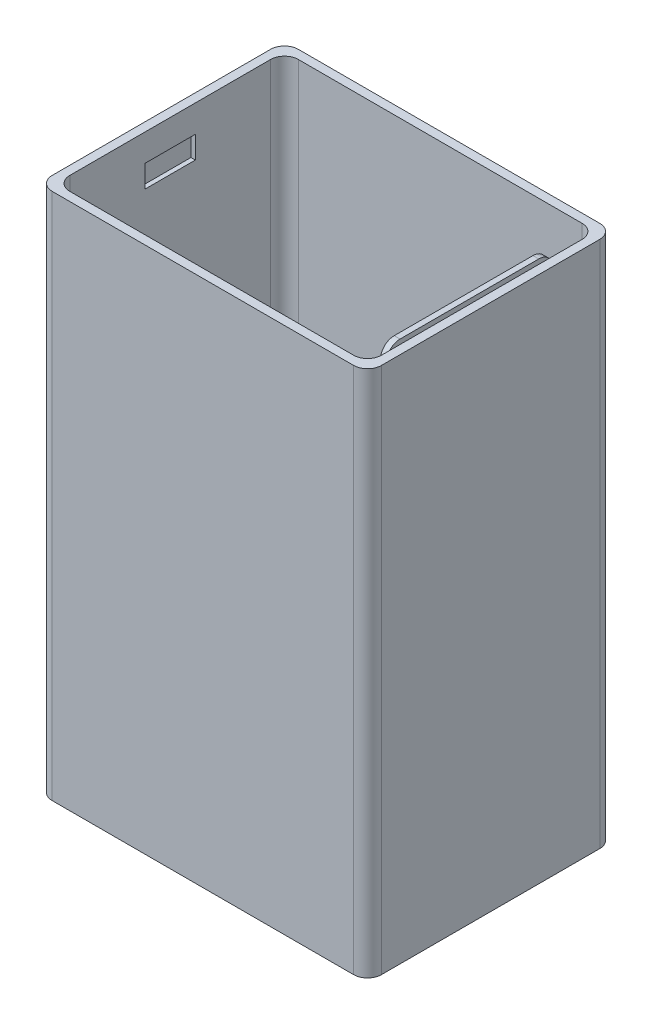
SolidWorks part; units mm, degrees
ref_plane "Front Plane" through (0, 0, 0) normal (0, 0, 1) x (1, 0, 0)
ref_plane "Top Plane" through (0, 0, 0) normal (0, 1, 0) x (1, 0, 0)
ref_plane "Right Plane" through (0, 0, 0) normal (1, 0, 0) x (0, 0, -1)
sketch "Sketch1" plane through (0, 0, 0) normal (0, 1, 0) x (1, 0, 0)
  line L0 (-6.35, 6.35) -> (-6.35, -171.3484)
  line L1 (0, 0) -> (224.9932, 0)
  line L2 (0, 0) -> (0, -164.9984)
  line L3 (0, -164.9984) -> (224.9932, -164.9984)
  line L4 (224.9932, 0) -> (224.9932, -164.9984)
  line L5 (-6.35, -171.3484) -> (231.3432, -171.3484)
  line L6 (231.3432, 6.35) -> (231.3432, -171.3484)
  line L7 (-6.35, 6.35) -> (231.3432, 6.35)
  dimension "D1" = 224.9932
  dimension "D2" = 164.9984
  dimension "D3" = 6.35
extrude "Boss-Extrude1" add sketch "Sketch1" along normal blind 374.65
sketch "Sketch4" plane through (224.9932, 0, 0) normal (-1, 0, 0) x (0, 0, 1)
  line L0 (164.9984, 0) -> (0, 0) construction
  line L1 (28.7274, 0) -> (136.1694, 0)
  line L2 (28.7274, 0) -> (28.7274, 374.65)
  line L3 (28.7274, 374.65) -> (136.1694, 374.65)
  line L4 (136.1694, 0) -> (136.1694, 374.65)
  line L5 (164.9984, 374.65) -> (0, 374.65) construction
  line L8 (164.9984, 374.65) -> (164.9984, 0) construction
  dimension "D1" = 107.442
  dimension "D2" = 28.829
extrude "Boss-Extrude2" add sketch "Sketch4" along normal blind 9.017
sketch "Sketch5" plane through (215.9762, 0, 0) normal (-1, 0, 0) x (0, 0, 1)
  line L0 (136.1694, 374.65) -> (28.7274, 374.65) construction
  line L5 (142.5194, 0) -> (22.3774, 0)
  line L6 (142.5194, 0) -> (142.5194, 374.65)
  line L7 (142.5194, 374.65) -> (22.3774, 374.65)
  line L8 (22.3774, 0) -> (22.3774, 374.65)
  line L9 (28.7274, 0) -> (136.1694, 0) construction
  line L11 (164.9984, 374.65) -> (164.9984, 0) construction
  line L12 (136.1694, 0) -> (136.1694, 374.65) construction
  line L13 (28.7274, 374.65) -> (28.7274, 0) construction
  point P5 (0, 0)
  dimension "D1" = 6.35
  dimension "D2" = 6.35
extrude "Boss-Extrude3" add sketch "Sketch5" along normal blind 4.191
sketch "Sketch7" plane through (0, 374.65, 0) normal (0, 1, 0) x (1, 0, 0)
  line L1 (215.9762, -136.1694) -> (224.9932, -136.1694)
  line L2 (215.9762, -136.1694) -> (215.9762, -28.7274)
  line L3 (215.9762, -28.7274) -> (224.9932, -28.7274)
  line L4 (224.9932, -136.1694) -> (224.9932, -28.7274)
extrude "Cut-Extrude1" cut sketch "Sketch7" against normal blind 21.59
sketch "Sketch10" plane through (0, 374.65, 0) normal (0, 1, 0) x (1, 0, 0)
  line L1 (211.7852, -142.5194) -> (215.9762, -142.5194)
  line L2 (211.7852, -142.5194) -> (211.7852, -22.3774)
  line L3 (211.7852, -22.3774) -> (215.9762, -22.3774)
  line L4 (215.9762, -142.5194) -> (215.9762, -22.3774)
extrude "Cut-Extrude2" cut sketch "Sketch10" against normal blind 5.588
fillet "Fillet1" radius 10 1 edges at (231.3432, 187.325, 171.3484)
fillet "Fillet2" radius 10 1 edges at (224.9932, 187.325, 164.9984)
fillet "Fillet3" radius 10 2 edges at (231.3432, 187.325, -6.35) (224.9932, 187.325, 0)
fillet "Fillet4" radius 10 2 edges at (-6.35, 187.325, 171.3484) (0, 187.325, 164.9984)
fillet "Fillet5" radius 10 2 edges at (0, 187.325, 0) (-6.35, 187.325, -6.35)
fillet "Fillet6" radius 10 2 edges at (220.4847, 353.06, 136.1694) (220.4847, 353.06, 28.7274)
fillet "Fillet7" radius 10 2 edges at (213.8807, 369.062, 22.3774) (213.8807, 369.062, 142.5194)
sketch "Sketch11" plane through (211.7852, 0, 0) normal (-1, 0, 0) x (0, 0, 1)
  line L0 (22.3774, 0) -> (142.5194, 0) construction
  line L1 (57.0484, 0) -> (107.8484, 0)
  line L2 (57.0484, 0) -> (57.0484, 15.24)
  line L3 (57.0484, 15.24) -> (107.8484, 15.24)
  line L4 (107.8484, 0) -> (107.8484, 15.24)
  line L5 (142.5194, 0) -> (142.5194, 359.062) construction
  dimension "D1" = 15.24
  dimension "D2" = 50.8
  dimension "D3" = 34.671
extrude "Boss-Extrude4" add sketch "Sketch11" along normal blind 19.9898
fillet "Fillet10" radius 10 2 edges at (191.7954, 7.62, 107.8484) (191.7954, 7.62, 57.0484)
fillet "Fillet11" radius 10 5 edges at (206.7903, 15.24, 107.8484) (194.7243, 15.24, 104.9195) (206.7903, 15.24, 57.0484) (194.7243, 15.24, 59.9773) (191.7954, 15.24, 82.4484)
sketch "Sketch12" plane through (0, 0, 0) normal (0, -1, 0) x (1, 0, 0)
  line L0 (231.3432, 161.3484) -> (231.3432, 3.65) construction
  line L1 (221.3432, -6.35) -> (3.65, -6.35) construction
  line L2 (-6.35, 3.65) -> (-6.35, 161.3484) construction
  line L3 (3.65, 171.3484) -> (221.3432, 171.3484) construction
  line L4 (231.3432, 161.3484) -> (231.3432, 3.65)
  line L5 (221.3432, -6.35) -> (3.65, -6.35)
  line L6 (-6.35, 3.65) -> (-6.35, 161.3484)
  line L7 (3.65, 171.3484) -> (221.3432, 171.3484)
  arc A0 (231.3432, 161.3484) -> (221.3432, 171.3484) centre (221.3432, 161.3484) ccw construction
  arc A1 (221.3432, -6.35) -> (231.3432, 3.65) centre (221.3432, 3.65) ccw construction
  arc A2 (-6.35, 3.65) -> (3.65, -6.35) centre (3.65, 3.65) ccw construction
  arc A3 (3.65, 171.3484) -> (-6.35, 161.3484) centre (3.65, 161.3484) ccw construction
  arc A4 (231.3432, 161.3484) -> (221.3432, 171.3484) centre (221.3432, 161.3484) ccw
  arc A5 (221.3432, -6.35) -> (231.3432, 3.65) centre (221.3432, 3.65) ccw
  arc A6 (-6.35, 3.65) -> (3.65, -6.35) centre (3.65, 3.65) ccw
  arc A7 (3.65, 171.3484) -> (-6.35, 161.3484) centre (3.65, 161.3484) ccw
extrude "Boss-Extrude5" add sketch "Sketch12" along normal blind 6.35
fillet "Fillet13" radius 10 9 edges at (224.9932, 0, 19.3637) (222.0643, 0, 2.9289) (112.4966, 0, 0) (2.9289, 0, 2.9289) (224.9932, 0, 145.5839) (222.0643, 0, 162.0695) (112.4966, 0, 164.9984) (2.9289, 0, 162.0695) (0, 0, 82.4992)
sketch "Sketch13" plane through (0, 0, 0) normal (1, 0, 0) x (0, 0, -1)
  line L0 (-10, 374.65) -> (-154.9984, 374.65) construction
  line L1 (-100.7542, 355.0412) -> (-64.356, 355.0412)
  line L2 (-100.7542, 355.0412) -> (-100.7542, 338.9122)
  line L3 (-100.7542, 338.9122) -> (-64.356, 338.9122)
  line L4 (-64.356, 355.0412) -> (-64.356, 338.9122)
  line L5 (-10, 10) -> (-10, 374.65) construction
  dimension "D1" = 19.6088
  dimension "D2" = 16.129
  dimension "D3" = 36.3982
  dimension "D4" = 54.356
extrude "Cut-Extrude4" cut sketch "Sketch13" against normal blind 3.175
sketch "Sketch15" plane through (0, -6.35, 0) normal (0, -1, 0) x (1, 0, 0)
  line L0 (177.8, 131.1399) -> (184.15, 134.8061)
  line L1 (196.85, 131.1399) -> (203.2, 134.8061)
  line L2 (203.2, 134.8061) -> (203.2, 142.1384)
  line L3 (203.2, 142.1384) -> (196.85, 145.8046)
  line L4 (196.85, 145.8046) -> (190.5, 142.1384)
  line L5 (190.5, 142.1384) -> (190.5, 134.8061)
  line L6 (190.5, 134.8061) -> (196.85, 131.1399)
  line L7 (171.45, 134.8061) -> (177.8, 131.1399)
  line L8 (171.45, 142.1384) -> (171.45, 134.8061)
  line L9 (177.8, 145.8046) -> (171.45, 142.1384)
  line L10 (184.15, 142.1384) -> (177.8, 145.8046)
  line L11 (184.15, 134.8061) -> (184.15, 142.1384)
  line L12 (158.75, 131.1399) -> (165.1, 134.8061)
  line L13 (152.4, 134.8061) -> (158.75, 131.1399)
  line L14 (152.4, 142.1384) -> (152.4, 134.8061)
  line L15 (158.75, 145.8046) -> (152.4, 142.1384)
  line L16 (165.1, 142.1384) -> (158.75, 145.8046)
  line L17 (165.1, 134.8061) -> (165.1, 142.1384)
  line L18 (139.7, 131.1399) -> (146.05, 134.8061)
  line L19 (133.35, 134.8061) -> (139.7, 131.1399)
  line L20 (133.35, 142.1384) -> (133.35, 134.8061)
  line L21 (139.7, 145.8046) -> (133.35, 142.1384)
  line L22 (146.05, 142.1384) -> (139.7, 145.8046)
  line L23 (146.05, 134.8061) -> (146.05, 142.1384)
  line L24 (120.65, 131.1399) -> (127, 134.8061)
  line L25 (114.3, 134.8061) -> (120.65, 131.1399)
  line L26 (114.3, 142.1384) -> (114.3, 134.8061)
  line L27 (120.65, 145.8046) -> (114.3, 142.1384)
  line L28 (127, 142.1384) -> (120.65, 145.8046)
  line L29 (127, 134.8061) -> (127, 142.1384)
  line L30 (-6.35, 161.3484) -> (-6.35, 3.65) construction
  line L31 (231.3432, 3.65) -> (231.3432, 161.3484) construction
  line L32 (3.65, -6.35) -> (221.3432, -6.35) construction
  line L38 (101.6, 131.1399) -> (107.95, 134.8061)
  line L39 (95.25, 134.8061) -> (101.6, 131.1399)
  line L40 (95.25, 142.1384) -> (95.25, 134.8061)
  line L41 (101.6, 145.8046) -> (95.25, 142.1384)
  line L42 (107.95, 142.1384) -> (101.6, 145.8046)
  line L43 (107.95, 134.8061) -> (107.95, 142.1384)
  line L44 (82.55, 131.1399) -> (88.9, 134.8061)
  line L45 (76.2, 134.8061) -> (82.55, 131.1399)
  line L46 (76.2, 142.1384) -> (76.2, 134.8061)
  line L47 (82.55, 145.8046) -> (76.2, 142.1384)
  line L48 (88.9, 142.1384) -> (82.55, 145.8046)
  line L49 (88.9, 134.8061) -> (88.9, 142.1384)
  line L50 (63.5, 131.1399) -> (69.85, 134.8061)
  line L51 (57.15, 134.8061) -> (63.5, 131.1399)
  line L52 (57.15, 142.1384) -> (57.15, 134.8061)
  line L53 (63.5, 145.8046) -> (57.15, 142.1384)
  line L54 (69.85, 142.1384) -> (63.5, 145.8046)
  line L55 (69.85, 134.8061) -> (69.85, 142.1384)
  line L56 (44.45, 131.1399) -> (50.8, 134.8061)
  line L57 (38.1, 134.8061) -> (44.45, 131.1399)
  line L58 (38.1, 142.1384) -> (38.1, 134.8061)
  line L59 (44.45, 145.8046) -> (38.1, 142.1384)
  line L60 (50.8, 142.1384) -> (44.45, 145.8046)
  line L61 (50.8, 134.8061) -> (50.8, 142.1384)
  line L62 (25.4, 131.1399) -> (31.75, 134.8061)
  line L63 (19.05, 134.8061) -> (25.4, 131.1399)
  line L64 (19.05, 142.1384) -> (19.05, 134.8061)
  line L65 (25.4, 145.8046) -> (19.05, 142.1384)
  line L66 (31.75, 142.1384) -> (25.4, 145.8046)
  line L67 (31.75, 134.8061) -> (31.75, 142.1384)
  line L74 (32.4716, 113.2256) -> (38.8216, 116.8918)
  line L75 (26.1216, 116.8918) -> (32.4716, 113.2256)
  line L76 (26.1216, 124.2241) -> (26.1216, 116.8918)
  line L77 (32.4716, 127.8903) -> (26.1216, 124.2241)
  line L78 (38.8216, 124.2241) -> (32.4716, 127.8903)
  line L79 (38.8216, 116.8918) -> (38.8216, 124.2241)
  line L80 (51.5216, 113.2256) -> (57.8716, 116.8918)
  line L81 (57.8716, 116.8918) -> (57.8716, 124.2241)
  line L82 (57.8716, 124.2241) -> (51.5216, 127.8903)
  line L83 (51.5216, 127.8903) -> (45.1716, 124.2241)
  line L84 (45.1716, 124.2241) -> (45.1716, 116.8918)
  line L85 (45.1716, 116.8918) -> (51.5216, 113.2256)
  line L86 (70.5716, 113.2256) -> (76.9216, 116.8918)
  line L87 (76.9216, 116.8918) -> (76.9216, 124.2241)
  line L88 (76.9216, 124.2241) -> (70.5716, 127.8903)
  line L89 (70.5716, 127.8903) -> (64.2216, 124.2241)
  line L90 (64.2216, 124.2241) -> (64.2216, 116.8918)
  line L91 (64.2216, 116.8918) -> (70.5716, 113.2256)
  line L92 (89.6216, 113.2256) -> (95.9716, 116.8918)
  line L93 (95.9716, 116.8918) -> (95.9716, 124.2241)
  line L94 (95.9716, 124.2241) -> (89.6216, 127.8903)
  line L95 (89.6216, 127.8903) -> (83.2716, 124.2241)
  line L96 (83.2716, 124.2241) -> (83.2716, 116.8918)
  line L97 (83.2716, 116.8918) -> (89.6216, 113.2256)
  line L98 (108.6716, 113.2256) -> (115.0216, 116.8918)
  line L99 (115.0216, 116.8918) -> (115.0216, 124.2241)
  line L100 (115.0216, 124.2241) -> (108.6716, 127.8903)
  line L101 (108.6716, 127.8903) -> (102.3216, 124.2241)
  line L102 (102.3216, 124.2241) -> (102.3216, 116.8918)
  line L103 (102.3216, 116.8918) -> (108.6716, 113.2256)
  line L104 (127.7216, 113.2256) -> (134.0716, 116.8918)
  line L105 (134.0716, 116.8918) -> (134.0716, 124.2241)
  line L106 (134.0716, 124.2241) -> (127.7216, 127.8903)
  line L107 (127.7216, 127.8903) -> (121.3716, 124.2241)
  line L108 (121.3716, 124.2241) -> (121.3716, 116.8918)
  line L109 (121.3716, 116.8918) -> (127.7216, 113.2256)
  line L110 (146.7716, 113.2256) -> (153.1216, 116.8918)
  line L111 (153.1216, 116.8918) -> (153.1216, 124.2241)
  line L112 (153.1216, 124.2241) -> (146.7716, 127.8903)
  line L113 (146.7716, 127.8903) -> (140.4216, 124.2241)
  line L114 (140.4216, 124.2241) -> (140.4216, 116.8918)
  line L115 (140.4216, 116.8918) -> (146.7716, 113.2256)
  line L116 (165.8216, 113.2256) -> (172.1716, 116.8918)
  line L117 (172.1716, 116.8918) -> (172.1716, 124.2241)
  line L118 (172.1716, 124.2241) -> (165.8216, 127.8903)
  line L119 (165.8216, 127.8903) -> (159.4716, 124.2241)
  line L120 (159.4716, 124.2241) -> (159.4716, 116.8918)
  line L121 (159.4716, 116.8918) -> (165.8216, 113.2256)
  line L122 (184.8716, 113.2256) -> (191.2216, 116.8918)
  line L123 (191.2216, 116.8918) -> (191.2216, 124.2241)
  line L124 (191.2216, 124.2241) -> (184.8716, 127.8903)
  line L125 (184.8716, 127.8903) -> (178.5216, 124.2241)
  line L126 (178.5216, 124.2241) -> (178.5216, 116.8918)
  line L127 (178.5216, 116.8918) -> (184.8716, 113.2256)
  line L128 (25.4, 95.3113) -> (31.75, 98.9775)
  line L129 (31.75, 98.9775) -> (31.75, 106.3099)
  line L130 (31.75, 106.3099) -> (25.4, 109.976)
  line L131 (25.4, 109.976) -> (19.05, 106.3099)
  line L132 (19.05, 106.3099) -> (19.05, 98.9775)
  line L133 (19.05, 98.9775) -> (25.4, 95.3113)
  line L134 (44.45, 95.3113) -> (50.8, 98.9775)
  line L135 (50.8, 98.9775) -> (50.8, 106.3099)
  line L136 (50.8, 106.3099) -> (44.45, 109.976)
  line L137 (44.45, 109.976) -> (38.1, 106.3099)
  line L138 (38.1, 106.3099) -> (38.1, 98.9775)
  line L139 (38.1, 98.9775) -> (44.45, 95.3113)
  line L140 (63.5, 95.3113) -> (69.85, 98.9775)
  line L141 (69.85, 98.9775) -> (69.85, 106.3099)
  line L142 (69.85, 106.3099) -> (63.5, 109.976)
  line L143 (63.5, 109.976) -> (57.15, 106.3099)
  line L144 (57.15, 106.3099) -> (57.15, 98.9775)
  line L145 (57.15, 98.9775) -> (63.5, 95.3113)
  line L146 (82.55, 95.3113) -> (88.9, 98.9775)
  line L147 (88.9, 98.9775) -> (88.9, 106.3099)
  line L148 (88.9, 106.3099) -> (82.55, 109.976)
  line L149 (82.55, 109.976) -> (76.2, 106.3099)
  line L150 (76.2, 106.3099) -> (76.2, 98.9775)
  line L151 (76.2, 98.9775) -> (82.55, 95.3113)
  line L152 (101.6, 95.3113) -> (107.95, 98.9775)
  line L153 (107.95, 98.9775) -> (107.95, 106.3099)
  line L154 (107.95, 106.3099) -> (101.6, 109.976)
  line L155 (101.6, 109.976) -> (95.25, 106.3099)
  line L156 (95.25, 106.3099) -> (95.25, 98.9775)
  line L157 (95.25, 98.9775) -> (101.6, 95.3113)
  line L158 (120.65, 95.3113) -> (127, 98.9775)
  line L159 (127, 98.9775) -> (127, 106.3099)
  line L160 (127, 106.3099) -> (120.65, 109.976)
  line L161 (120.65, 109.976) -> (114.3, 106.3099)
  line L162 (114.3, 106.3099) -> (114.3, 98.9775)
  line L163 (114.3, 98.9775) -> (120.65, 95.3113)
  line L164 (139.7, 95.3113) -> (146.05, 98.9775)
  line L165 (146.05, 98.9775) -> (146.05, 106.3099)
  line L166 (146.05, 106.3099) -> (139.7, 109.976)
  line L167 (139.7, 109.976) -> (133.35, 106.3099)
  line L168 (133.35, 106.3099) -> (133.35, 98.9775)
  line L169 (133.35, 98.9775) -> (139.7, 95.3113)
  line L170 (158.75, 95.3113) -> (165.1, 98.9775)
  line L171 (165.1, 98.9775) -> (165.1, 106.3099)
  line L172 (165.1, 106.3099) -> (158.75, 109.976)
  line L173 (158.75, 109.976) -> (152.4, 106.3099)
  line L174 (152.4, 106.3099) -> (152.4, 98.9775)
  line L175 (152.4, 98.9775) -> (158.75, 95.3113)
  line L176 (177.8, 95.3113) -> (184.15, 98.9775)
  line L177 (184.15, 98.9775) -> (184.15, 106.3099)
  line L178 (184.15, 106.3099) -> (177.8, 109.976)
  line L179 (177.8, 109.976) -> (171.45, 106.3099)
  line L180 (171.45, 106.3099) -> (171.45, 98.9775)
  line L181 (171.45, 98.9775) -> (177.8, 95.3113)
  line L188 (184.8716, 77.3971) -> (191.2216, 81.0632)
  line L189 (191.2216, 81.0632) -> (191.2216, 88.3956)
  line L190 (191.2216, 88.3956) -> (184.8716, 92.0618)
  line L191 (184.8716, 92.0618) -> (178.5216, 88.3956)
  line L192 (178.5216, 88.3956) -> (178.5216, 81.0632)
  line L193 (178.5216, 81.0632) -> (184.8716, 77.3971)
  line L194 (165.8216, 77.3971) -> (172.1716, 81.0632)
  line L195 (172.1716, 81.0632) -> (172.1716, 88.3956)
  line L196 (172.1716, 88.3956) -> (165.8216, 92.0618)
  line L197 (165.8216, 92.0618) -> (159.4716, 88.3956)
  line L198 (159.4716, 88.3956) -> (159.4716, 81.0632)
  line L199 (159.4716, 81.0632) -> (165.8216, 77.3971)
  line L200 (146.7716, 77.3971) -> (153.1216, 81.0632)
  line L201 (153.1216, 81.0632) -> (153.1216, 88.3956)
  line L202 (153.1216, 88.3956) -> (146.7716, 92.0618)
  line L203 (146.7716, 92.0618) -> (140.4216, 88.3956)
  line L204 (140.4216, 88.3956) -> (140.4216, 81.0632)
  line L205 (140.4216, 81.0632) -> (146.7716, 77.3971)
  line L206 (127.7216, 77.3971) -> (134.0716, 81.0632)
  line L207 (134.0716, 81.0632) -> (134.0716, 88.3956)
  line L208 (134.0716, 88.3956) -> (127.7216, 92.0618)
  line L209 (127.7216, 92.0618) -> (121.3716, 88.3956)
  line L210 (121.3716, 88.3956) -> (121.3716, 81.0632)
  line L211 (121.3716, 81.0632) -> (127.7216, 77.3971)
  line L212 (108.6716, 77.3971) -> (115.0216, 81.0632)
  line L213 (115.0216, 81.0632) -> (115.0216, 88.3956)
  line L214 (115.0216, 88.3956) -> (108.6716, 92.0618)
  line L215 (108.6716, 92.0618) -> (102.3216, 88.3956)
  line L216 (102.3216, 88.3956) -> (102.3216, 81.0632)
  line L217 (102.3216, 81.0632) -> (108.6716, 77.3971)
  line L218 (89.6216, 77.3971) -> (95.9716, 81.0632)
  line L219 (95.9716, 81.0632) -> (95.9716, 88.3956)
  line L220 (95.9716, 88.3956) -> (89.6216, 92.0618)
  line L221 (89.6216, 92.0618) -> (83.2716, 88.3956)
  line L222 (83.2716, 88.3956) -> (83.2716, 81.0632)
  line L223 (83.2716, 81.0632) -> (89.6216, 77.3971)
  line L224 (70.5716, 77.3971) -> (76.9216, 81.0632)
  line L225 (76.9216, 81.0632) -> (76.9216, 88.3956)
  line L226 (76.9216, 88.3956) -> (70.5716, 92.0618)
  line L227 (70.5716, 92.0618) -> (64.2216, 88.3956)
  line L228 (64.2216, 88.3956) -> (64.2216, 81.0632)
  line L229 (64.2216, 81.0632) -> (70.5716, 77.3971)
  line L230 (51.5216, 77.3971) -> (57.8716, 81.0632)
  line L231 (57.8716, 81.0632) -> (57.8716, 88.3956)
  line L232 (57.8716, 88.3956) -> (51.5216, 92.0618)
  line L233 (51.5216, 92.0618) -> (45.1716, 88.3956)
  line L234 (45.1716, 88.3956) -> (45.1716, 81.0632)
  line L235 (45.1716, 81.0632) -> (51.5216, 77.3971)
  line L236 (32.4716, 77.3971) -> (38.8216, 81.0632)
  line L237 (38.8216, 81.0632) -> (38.8216, 88.3956)
  line L238 (38.8216, 88.3956) -> (32.4716, 92.0618)
  line L239 (32.4716, 92.0618) -> (26.1216, 88.3956)
  line L240 (26.1216, 88.3956) -> (26.1216, 81.0632)
  line L241 (26.1216, 81.0632) -> (32.4716, 77.3971)
  line L242 (25.4, 59.4828) -> (31.75, 63.149)
  line L243 (31.75, 63.149) -> (31.75, 70.4813)
  line L244 (31.75, 70.4813) -> (25.4, 74.1475)
  line L245 (25.4, 74.1475) -> (19.05, 70.4813)
  line L246 (19.05, 70.4813) -> (19.05, 63.149)
  line L247 (19.05, 63.149) -> (25.4, 59.4828)
  line L248 (44.45, 59.4828) -> (50.8, 63.149)
  line L249 (50.8, 63.149) -> (50.8, 70.4813)
  line L250 (50.8, 70.4813) -> (44.45, 74.1475)
  line L251 (44.45, 74.1475) -> (38.1, 70.4813)
  line L252 (38.1, 70.4813) -> (38.1, 63.149)
  line L253 (38.1, 63.149) -> (44.45, 59.4828)
  line L254 (63.5, 59.4828) -> (69.85, 63.149)
  line L255 (69.85, 63.149) -> (69.85, 70.4813)
  line L256 (69.85, 70.4813) -> (63.5, 74.1475)
  line L257 (63.5, 74.1475) -> (57.15, 70.4813)
  line L258 (57.15, 70.4813) -> (57.15, 63.149)
  line L259 (57.15, 63.149) -> (63.5, 59.4828)
  line L260 (82.55, 59.4828) -> (88.9, 63.149)
  line L261 (88.9, 63.149) -> (88.9, 70.4813)
  line L262 (88.9, 70.4813) -> (82.55, 74.1475)
  line L263 (82.55, 74.1475) -> (76.2, 70.4813)
  line L264 (76.2, 70.4813) -> (76.2, 63.149)
  line L265 (76.2, 63.149) -> (82.55, 59.4828)
  line L266 (101.6, 59.4828) -> (107.95, 63.149)
  line L267 (107.95, 63.149) -> (107.95, 70.4813)
  line L268 (107.95, 70.4813) -> (101.6, 74.1475)
  line L269 (101.6, 74.1475) -> (95.25, 70.4813)
  line L270 (95.25, 70.4813) -> (95.25, 63.149)
  line L271 (95.25, 63.149) -> (101.6, 59.4828)
  line L272 (120.65, 59.4828) -> (127, 63.149)
  line L273 (127, 63.149) -> (127, 70.4813)
  line L274 (127, 70.4813) -> (120.65, 74.1475)
  line L275 (120.65, 74.1475) -> (114.3, 70.4813)
  line L276 (114.3, 70.4813) -> (114.3, 63.149)
  line L277 (114.3, 63.149) -> (120.65, 59.4828)
  line L278 (139.7, 59.4828) -> (146.05, 63.149)
  line L279 (146.05, 63.149) -> (146.05, 70.4813)
  line L280 (146.05, 70.4813) -> (139.7, 74.1475)
  line L281 (139.7, 74.1475) -> (133.35, 70.4813)
  line L282 (133.35, 70.4813) -> (133.35, 63.149)
  line L283 (133.35, 63.149) -> (139.7, 59.4828)
  line L284 (158.75, 59.4828) -> (165.1, 63.149)
  line L285 (165.1, 63.149) -> (165.1, 70.4813)
  line L286 (165.1, 70.4813) -> (158.75, 74.1475)
  line L287 (158.75, 74.1475) -> (152.4, 70.4813)
  line L288 (152.4, 70.4813) -> (152.4, 63.149)
  line L289 (152.4, 63.149) -> (158.75, 59.4828)
  line L290 (177.8, 59.4828) -> (184.15, 63.149)
  line L291 (184.15, 63.149) -> (184.15, 70.4813)
  line L292 (184.15, 70.4813) -> (177.8, 74.1475)
  line L293 (177.8, 74.1475) -> (171.45, 70.4813)
  line L294 (171.45, 70.4813) -> (171.45, 63.149)
  line L295 (171.45, 63.149) -> (177.8, 59.4828)
  line L302 (184.8716, 41.5685) -> (191.2216, 45.2347)
  line L303 (191.2216, 45.2347) -> (191.2216, 52.567)
  line L304 (191.2216, 52.567) -> (184.8716, 56.2332)
  line L305 (184.8716, 56.2332) -> (178.5216, 52.567)
  line L306 (178.5216, 52.567) -> (178.5216, 45.2347)
  line L307 (178.5216, 45.2347) -> (184.8716, 41.5685)
  line L308 (165.8216, 41.5685) -> (172.1716, 45.2347)
  line L309 (172.1716, 45.2347) -> (172.1716, 52.567)
  line L310 (172.1716, 52.567) -> (165.8216, 56.2332)
  line L311 (165.8216, 56.2332) -> (159.4716, 52.567)
  line L312 (159.4716, 52.567) -> (159.4716, 45.2347)
  line L313 (159.4716, 45.2347) -> (165.8216, 41.5685)
  line L314 (146.7716, 41.5685) -> (153.1216, 45.2347)
  line L315 (153.1216, 45.2347) -> (153.1216, 52.567)
  line L316 (153.1216, 52.567) -> (146.7716, 56.2332)
  line L317 (146.7716, 56.2332) -> (140.4216, 52.567)
  line L318 (140.4216, 52.567) -> (140.4216, 45.2347)
  line L319 (140.4216, 45.2347) -> (146.7716, 41.5685)
  line L320 (127.7216, 41.5685) -> (134.0716, 45.2347)
  line L321 (134.0716, 45.2347) -> (134.0716, 52.567)
  line L322 (134.0716, 52.567) -> (127.7216, 56.2332)
  line L323 (127.7216, 56.2332) -> (121.3716, 52.567)
  line L324 (121.3716, 52.567) -> (121.3716, 45.2347)
  line L325 (121.3716, 45.2347) -> (127.7216, 41.5685)
  line L326 (108.6716, 41.5685) -> (115.0216, 45.2347)
  line L327 (115.0216, 45.2347) -> (115.0216, 52.567)
  line L328 (115.0216, 52.567) -> (108.6716, 56.2332)
  line L329 (108.6716, 56.2332) -> (102.3216, 52.567)
  line L330 (102.3216, 52.567) -> (102.3216, 45.2347)
  line L331 (102.3216, 45.2347) -> (108.6716, 41.5685)
  line L332 (89.6216, 41.5685) -> (95.9716, 45.2347)
  line L333 (95.9716, 45.2347) -> (95.9716, 52.567)
  line L334 (95.9716, 52.567) -> (89.6216, 56.2332)
  line L335 (89.6216, 56.2332) -> (83.2716, 52.567)
  line L336 (83.2716, 52.567) -> (83.2716, 45.2347)
  line L337 (83.2716, 45.2347) -> (89.6216, 41.5685)
  line L338 (70.5716, 41.5685) -> (76.9216, 45.2347)
  line L339 (76.9216, 45.2347) -> (76.9216, 52.567)
  line L340 (76.9216, 52.567) -> (70.5716, 56.2332)
  line L341 (70.5716, 56.2332) -> (64.2216, 52.567)
  line L342 (64.2216, 52.567) -> (64.2216, 45.2347)
  line L343 (64.2216, 45.2347) -> (70.5716, 41.5685)
  line L344 (51.5216, 41.5685) -> (57.8716, 45.2347)
  line L345 (57.8716, 45.2347) -> (57.8716, 52.567)
  line L346 (57.8716, 52.567) -> (51.5216, 56.2332)
  line L347 (51.5216, 56.2332) -> (45.1716, 52.567)
  line L348 (45.1716, 52.567) -> (45.1716, 45.2347)
  line L349 (45.1716, 45.2347) -> (51.5216, 41.5685)
  line L350 (32.4716, 41.5685) -> (38.8216, 45.2347)
  line L351 (38.8216, 45.2347) -> (38.8216, 52.567)
  line L352 (38.8216, 52.567) -> (32.4716, 56.2332)
  line L353 (32.4716, 56.2332) -> (26.1216, 52.567)
  line L354 (26.1216, 52.567) -> (26.1216, 45.2347)
  line L355 (26.1216, 45.2347) -> (32.4716, 41.5685)
  line L356 (25.4, 23.6542) -> (31.75, 27.3204)
  line L357 (31.75, 27.3204) -> (31.75, 34.6528)
  line L358 (31.75, 34.6528) -> (25.4, 38.3189)
  line L359 (25.4, 38.3189) -> (19.05, 34.6528)
  line L360 (19.05, 34.6528) -> (19.05, 27.3204)
  line L361 (19.05, 27.3204) -> (25.4, 23.6542)
  line L362 (44.45, 23.6542) -> (50.8, 27.3204)
  line L363 (50.8, 27.3204) -> (50.8, 34.6528)
  line L364 (50.8, 34.6528) -> (44.45, 38.3189)
  line L365 (44.45, 38.3189) -> (38.1, 34.6528)
  line L366 (38.1, 34.6528) -> (38.1, 27.3204)
  line L367 (38.1, 27.3204) -> (44.45, 23.6542)
  line L368 (63.5, 23.6542) -> (69.85, 27.3204)
  line L369 (69.85, 27.3204) -> (69.85, 34.6528)
  line L370 (69.85, 34.6528) -> (63.5, 38.3189)
  line L371 (63.5, 38.3189) -> (57.15, 34.6528)
  line L372 (57.15, 34.6528) -> (57.15, 27.3204)
  line L373 (57.15, 27.3204) -> (63.5, 23.6542)
  line L374 (82.55, 23.6542) -> (88.9, 27.3204)
  line L375 (88.9, 27.3204) -> (88.9, 34.6528)
  line L376 (88.9, 34.6528) -> (82.55, 38.3189)
  line L377 (82.55, 38.3189) -> (76.2, 34.6528)
  line L378 (76.2, 34.6528) -> (76.2, 27.3204)
  line L379 (76.2, 27.3204) -> (82.55, 23.6542)
  line L380 (101.6, 23.6542) -> (107.95, 27.3204)
  line L381 (107.95, 27.3204) -> (107.95, 34.6528)
  line L382 (107.95, 34.6528) -> (101.6, 38.3189)
  line L383 (101.6, 38.3189) -> (95.25, 34.6528)
  line L384 (95.25, 34.6528) -> (95.25, 27.3204)
  line L385 (95.25, 27.3204) -> (101.6, 23.6542)
  line L386 (120.65, 23.6542) -> (127, 27.3204)
  line L387 (127, 27.3204) -> (127, 34.6528)
  line L388 (127, 34.6528) -> (120.65, 38.3189)
  line L389 (120.65, 38.3189) -> (114.3, 34.6528)
  line L390 (114.3, 34.6528) -> (114.3, 27.3204)
  line L391 (114.3, 27.3204) -> (120.65, 23.6542)
  line L392 (139.7, 23.6542) -> (146.05, 27.3204)
  line L393 (146.05, 27.3204) -> (146.05, 34.6528)
  line L394 (146.05, 34.6528) -> (139.7, 38.3189)
  line L395 (139.7, 38.3189) -> (133.35, 34.6528)
  line L396 (133.35, 34.6528) -> (133.35, 27.3204)
  line L397 (133.35, 27.3204) -> (139.7, 23.6542)
  line L398 (158.75, 23.6542) -> (165.1, 27.3204)
  line L399 (165.1, 27.3204) -> (165.1, 34.6528)
  line L400 (165.1, 34.6528) -> (158.75, 38.3189)
  line L401 (158.75, 38.3189) -> (152.4, 34.6528)
  line L402 (152.4, 34.6528) -> (152.4, 27.3204)
  line L403 (152.4, 27.3204) -> (158.75, 23.6542)
  line L404 (177.8, 23.6542) -> (184.15, 27.3204)
  line L405 (184.15, 27.3204) -> (184.15, 34.6528)
  line L406 (184.15, 34.6528) -> (177.8, 38.3189)
  line L407 (177.8, 38.3189) -> (171.45, 34.6528)
  line L408 (171.45, 34.6528) -> (171.45, 27.3204)
  line L409 (171.45, 27.3204) -> (177.8, 23.6542)
  line L410 (196.85, 23.6542) -> (203.2, 27.3204)
  line L411 (203.2, 27.3204) -> (203.2, 34.6528)
  line L412 (203.2, 34.6528) -> (196.85, 38.3189)
  line L413 (196.85, 38.3189) -> (190.5, 34.6528)
  line L414 (190.5, 34.6528) -> (190.5, 27.3204)
  line L415 (190.5, 27.3204) -> (196.85, 23.6542)
  line L416 (190.5, 106.3099) -> (190.5, 98.9775) [skipped]
  line L417 (190.5, 98.9775) -> (196.85, 95.3113) [skipped]
  line L418 (196.85, 95.3113) -> (203.2, 98.9775) [skipped]
  line L419 (203.2, 98.9775) -> (203.2, 106.3099) [skipped]
  line L420 (203.2, 106.3099) -> (196.85, 109.976) [skipped]
  line L421 (196.85, 109.976) -> (190.5, 106.3099) [skipped]
  line L422 (203.2, 63.149) -> (203.2, 70.4813) [skipped]
  line L423 (196.85, 59.4828) -> (203.2, 63.149) [skipped]
  line L424 (190.5, 63.149) -> (196.85, 59.4828) [skipped]
  line L425 (190.5, 70.4813) -> (190.5, 63.149) [skipped]
  line L426 (196.85, 74.1475) -> (190.5, 70.4813) [skipped]
  line L427 (203.2, 70.4813) -> (196.85, 74.1475) [skipped]
  circle A0 centre (196.85, 138.4722) radius 6.35 construction
  dimension "D2" = 25.4
  dimension "D4" = 6.35
  dimension "D5" = 6.35
  dimension "D7" = 28.1432
  dimension "D8" = 7.3323
  dimension "D10" = 6.35
  dimension "D12" = 6.35
  dimension "D13" = 30.0042
  dimension "D14" = 40.1216
  dimension "D15" = 32.4716
  dimension "D16" = 6.35
  dimension "D17" = 9.525
  dimension "D18" = 9.525
  dimension "D3" = 10
  dimension "D6" = 9
  dimension "D9" = 3
  dimension "D11" = 2
sketch "Sketch17" plane through (0, -6.35, 0) normal (0, -1, 0) x (1, 0, 0)
extrude "Cut-Extrude5" cut sketch "Sketch15" against normal blind 6.35
